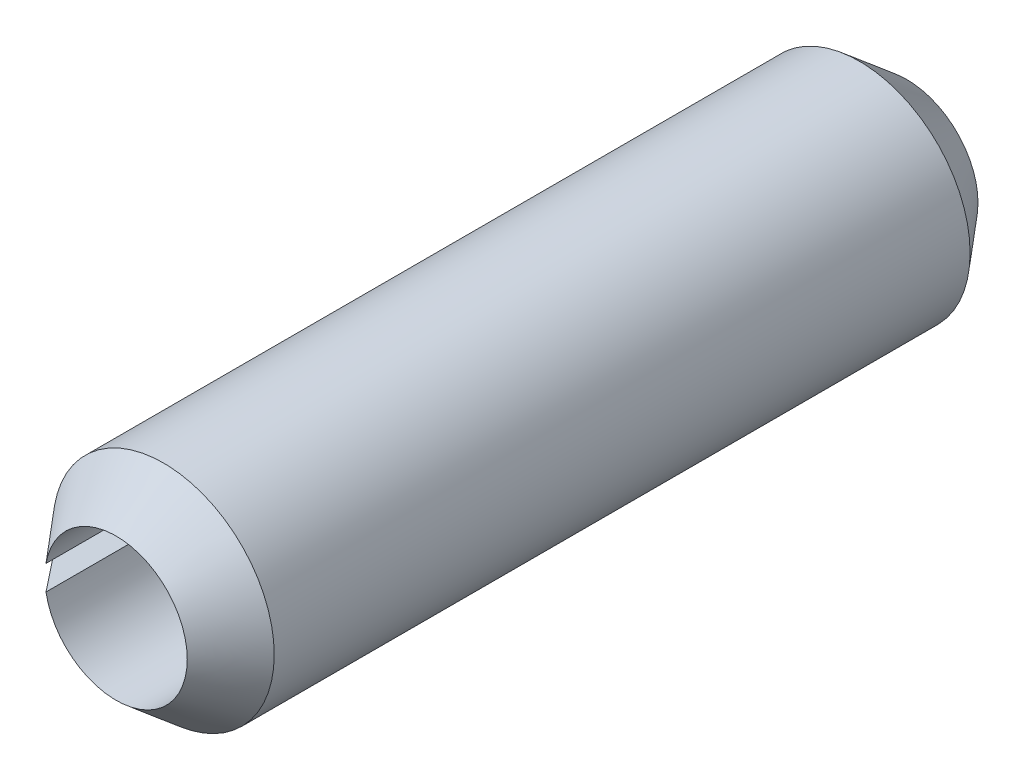
SolidWorks part; units mm, degrees
material "AISI 304"
ref_plane "Front Plane" through (0, 0, 0) normal (0, 0, 1) x (1, 0, 0)
ref_plane "Top Plane" through (0, 0, 0) normal (0, 1, 0) x (1, 0, 0)
ref_plane "Right Plane" through (0, 0, 0) normal (1, 0, 0) x (0, 0, -1)
sketch "Sketch1" plane through (0, 0, 0) normal (0, 0, 1) x (1, 0, 0)
  line L0 (0.9, 0) -> (1.4, 0) construction
  line L1 (-1.3787, 0.2431) -> (-0.8863, 0.1563)
  line L2 (-0.8863, -0.1563) -> (-1.3787, -0.2431)
  arc A0 (-1.3787, -0.2431) -> (-1.3787, 0.2431) centre (0, 0) ccw
  arc A1 (-0.8863, -0.1563) -> (-0.8863, 0.1563) centre (0, 0) ccw
  dimension "OD" = 2.8
  dimension "Wall thickness" = 0.5
  dimension "D3" = 20
extrude "Extrude1" add sketch "Sketch1" along normal mid plane 10
sketch "Sketch2" plane through (0, 0, 0) normal (1, 0, 0) x (0, 0, -1)
  line L0 (0, -1.4) -> (0, 1.4) construction
  line L1 (5, 0) -> (-5, 0) construction
  line L2 (5, -0.9) -> (5, 0.9) construction
  line L3 (5, 1.4) -> (-5, 1.4) construction
  line L4 (5, 1.4) -> (5, 0.9)
  line L5 (5, 0.9) -> (4.4, 1.4)
  line L6 (4.4, 1.4) -> (5, 1.4)
  line L7 (5, -1.4) -> (5, 1.4) construction
  line L8 (-4.4, 1.4) -> (-5, 1.4)
  line L9 (-5, 0.9) -> (-4.4, 1.4)
  line L10 (-5, 1.4) -> (-5, 0.9)
  line L11 (4.4, -1.4) -> (5, -1.4) construction
  line L12 (5, -0.9) -> (4.4, -1.4) construction
  line L13 (5, -1.4) -> (5, -0.9) construction
  dimension "B" = 1.8
  dimension "Chamfer max" = 0.6
revolve "Cut-Revolve1" cut sketch "Sketch2" angle 360 about L1
sketch "Sketch3" plane through (0, 0, 0) normal (0, 0, 1) x (1, 0, 0)
  line L0 (0.9, 0) -> (1.4, 0) construction
  line L1 (0.9, 0) -> (1.4, 0)
  circle A0 centre (0, 0) radius 1.4
  circle A1 centre (0, 0) radius 0.9
  arc A2 (-1.3787, -0.2431) -> (-1.3787, 0.2431) centre (0, 0) ccw construction
  arc A3 (-0.8863, -0.1563) -> (-0.8863, 0.1563) centre (0, 0) ccw construction
